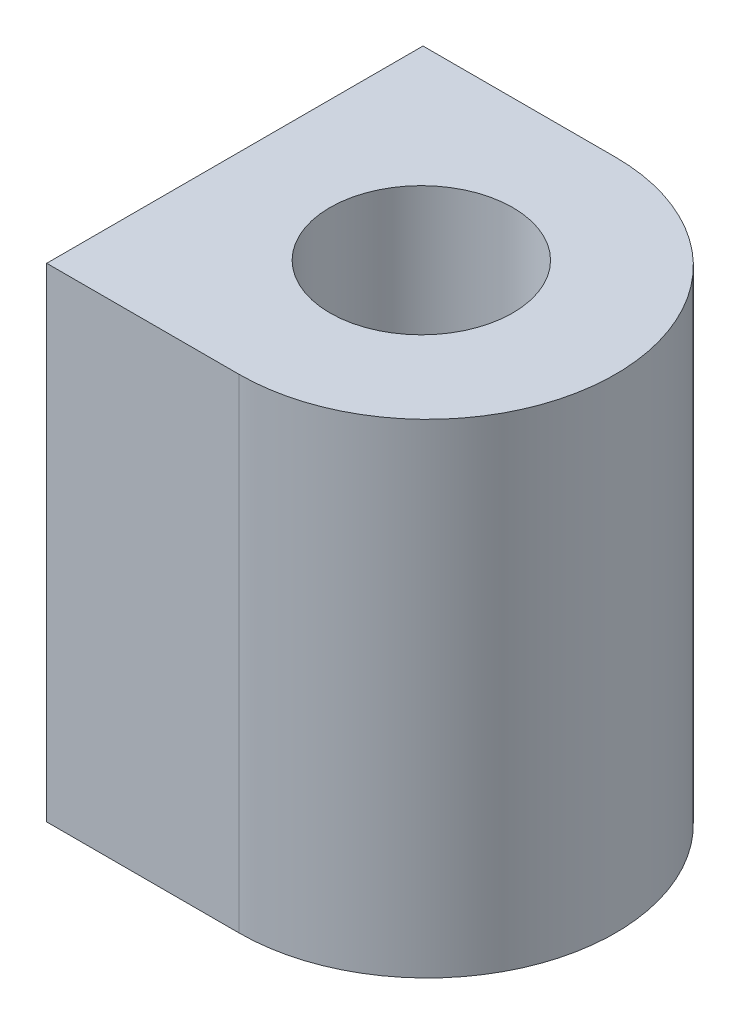
SolidWorks part; units mm, degrees
ref_plane "Front Plane" through (0, 0, 0) normal (0, 0, 1) x (1, 0, 0)
ref_plane "Top Plane" through (0, 0, 0) normal (0, 1, 0) x (1, 0, 0)
ref_plane "Right Plane" through (0, 0, 0) normal (1, 0, 0) x (0, 0, -1)
sketch "Sketch1" plane through (0, 0, 0) normal (0, 1, 0) x (1, 0, 0)
  line L0 (-3.4358, -0.0334) -> (-3.4358, 3.4666)
  line L1 (-3.4358, -0.0334) -> (-3.4358, -3.5334)
  line L5 (-3.4358, -3.5334) -> (0.1437, -3.5334)
  line L6 (-3.4358, 3.4666) -> (0.1437, 3.4666)
  circle A2 centre (0, 0) radius 1.7
  arc A4 (0.1437, 3.4666) -> (0.1437, -3.5334) centre (0.1437, -0.0334) cw
  dimension "D1" = 3.4
  dimension "D2" = 3.5
extrude "Boss-Extrude2" add sketch "Sketch1" along normal blind 9
